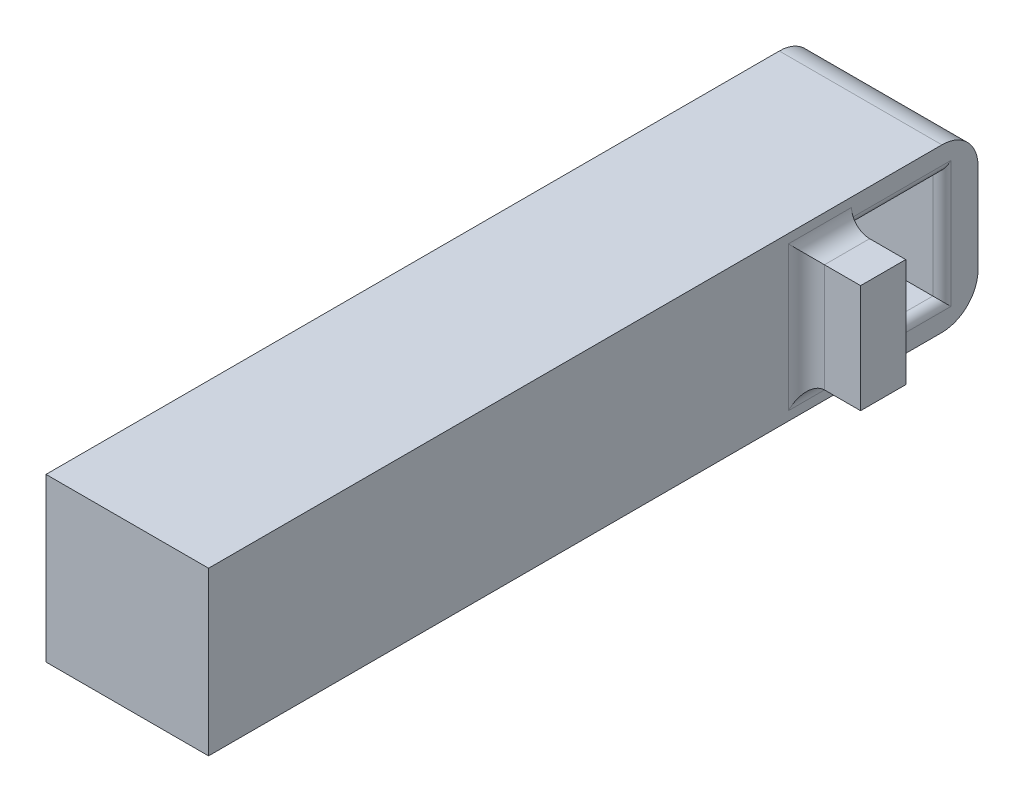
SolidWorks part; units mm, degrees
material "Custom Plastic"
ref_plane "Front Plane" through (0, 0, 0) normal (0, 0, 1) x (1, 0, 0)
ref_plane "Top Plane" through (0, 0, 0) normal (0, 1, 0) x (1, 0, 0)
ref_plane "Right Plane" through (0, 0, 0) normal (1, 0, 0) x (0, 0, -1)
sketch "Sketch1" plane through (0, 0, 0) normal (1, 0, 0) x (0, 0, -1)
  line L0 (50.8, 0) -> (50.8, 18) construction
  line L1 (0, 0) -> (85.2, 0)
  line L2 (0, 0) -> (0, 18)
  line L3 (0, 18) -> (85.2, 18)
  line L4 (85.2, 0) -> (85.2, 18)
  line L5 (81.2, 3) -> (71.2, 3)
  line L6 (81.2, 3) -> (81.2, 15)
  line L7 (81.2, 15) -> (71.2, 15)
  line L8 (71.2, 3) -> (71.2, 15)
  point P9 (85.2, 9)
  point P11 (81.2, 9)
  point P13 (76.2, 3)
  dimension "D1" = 10
  dimension "D2" = 12
  dimension "D4" = 4
  dimension "D3" = 3
  dimension "D5" = 25.4
  dimension "D6" = 50.8
extrude "Boss-Extrude1" add sketch "Sketch1" along normal mid plane 18
sketch "Sketch2" plane through (9, 0, 0) normal (1, 0, 0) x (0, 0, -1)
  line L1 (71.2, 3) -> (66.2, 3)
  line L2 (71.2, 3) -> (71.2, 15)
  line L3 (71.2, 15) -> (66.2, 15)
  line L4 (66.2, 3) -> (66.2, 15)
  point P5 (71.2, 15)
  dimension "D1" = 5
extrude "Boss-Extrude2" add sketch "Sketch2" along normal blind 6
fillet "Fillet1" radius 2 3 edges at (9, 9, -66.2) (9, 15, -68.7) (9, 3, -68.7)
fillet "Fillet2" radius 1 3 edges at (9, 3, -76.2) (9, 9, -81.2) (9, 15, -76.2)
fillet "Fillet3" radius 4 2 edges at (0, 0, -85.2) (0, 18, -85.2)
equation "\"D5@Sketch1\"=1in"
equation "\"D6@Sketch1\"=2in"
equation "\"D1@Boss-Extrude1\"=.75in"
equation "\"D1@Boss-Extrude2\"=24-18"
